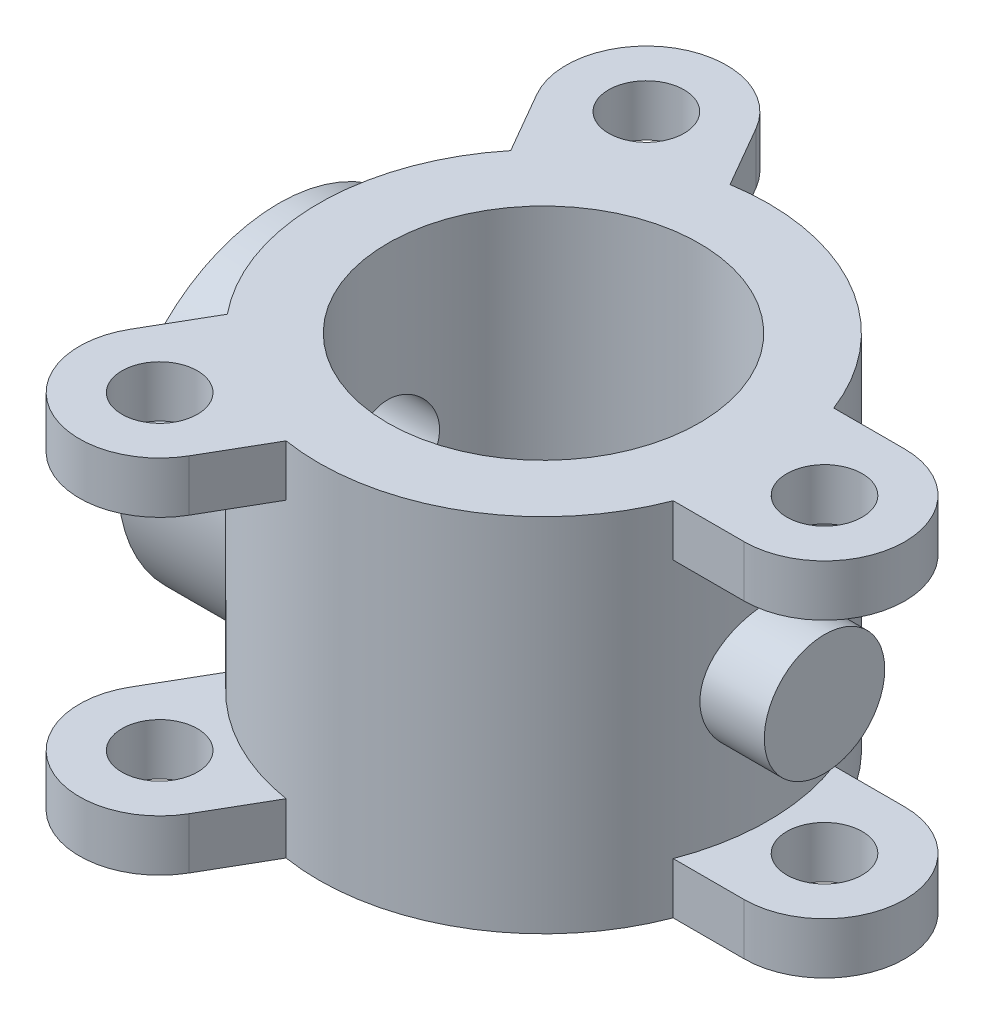
SolidWorks part; units mm, degrees
ref_plane "Front Plane" through (0, 0, 0) normal (0, 0, 1) x (1, 0, 0)
ref_plane "Top Plane" through (0, 0, 0) normal (0, 1, 0) x (1, 0, 0)
ref_plane "Right Plane" through (0, 0, 0) normal (1, 0, 0) x (0, 0, -1)
sketch "Sketch1" plane through (0, 0, 0) normal (0, 1, 0) x (1, 0, 0)
  circle A0 centre (0, 0) radius 97
  circle A1 centre (0, 0) radius 140
  dimension "D1" = 194
  dimension "D2" = 280
extrude "Boss-Extrude1" add sketch "Sketch1" along normal mid plane 225
sketch "Sketch2" plane through (0, 112.5, 0) normal (0, 1, 0) x (1, 0, 0)
  line L0 (0, 0) -> (50000, 0) construction
  line L1 (175, 50) -> (130.767, 50)
  line L2 (175, -50) -> (130.767, -50)
  circle A0 centre (175, 0) radius 23.5
  arc A1 (175, -50) -> (175, 50) centre (175, 0) ccw
  circle A2 centre (0, 0) radius 140 construction
  arc A3 (130.767, -50) -> (130.767, 50) centre (0, 0) ccw
  dimension "D1" = 100
  dimension "D2" = 47
  dimension "D3" = 175
extrude "Boss-Extrude2" add sketch "Sketch2" against normal blind 32
pattern_circular "CirPattern1" count 3 over 360 about axis through (0, 0, 0) along (0, 1, 0) of "Boss-Extrude2"
mirror "Mirror1" about plane through (0, 0, 0) normal (0, 1, 0) of "CirPattern1", "Boss-Extrude2"
sketch "Sketch3" plane through (0, 0, 0) normal (1, 0, 0) x (0, 0, -1)
  circle A0 centre (0, 0) radius 100
  dimension "D1" = 200
extrude "Boss-Extrude3" add sketch "Sketch3" along normal up to surface (67.0204 mm away) from offset 165 offset against normal yes
sketch "Sketch4" plane through (0, 0, 0) normal (1, 0, 0) x (0, 0, -1)
  circle A0 centre (0, 0) radius 37.5
  dimension "D1" = 75
extrude "Boss-Extrude4" add sketch "Sketch4" against normal up to surface (40.1158 mm away) from offset 175
sketch "Sketch5" plane through (-165, 0, 0) normal (-1, 0, 0) x (0, 0, 1)
  circle A0 centre (0, 0) radius 50
  dimension "D1" = 100
extrude "Cut-Extrude1" cut sketch "Sketch5" against normal blind 25
sketch "Sketch6" plane through (-165, 0, 0) normal (-1, 0, 0) x (0, 0, 1)
  circle A0 centre (0, 0) radius 28.1
  dimension "D1" = 56.2
extrude "Cut-Extrude2" cut sketch "Sketch6" against normal blind 310
sketch "Sketch9" plane through (-165, 0, 0) normal (-1, 0, 0) x (0, 0, 1)
  circle A0 centre (0, 75) radius 10.15
  dimension "D1" = 20.3
  dimension "D2" = 75
extrude "Cut-Extrude3" cut sketch "Sketch9" against normal blind 15
pattern_circular "CirPattern2" count 3 over 360 about axis through (0, 0, 0) along (1, 0, 0) of "Cut-Extrude3"
